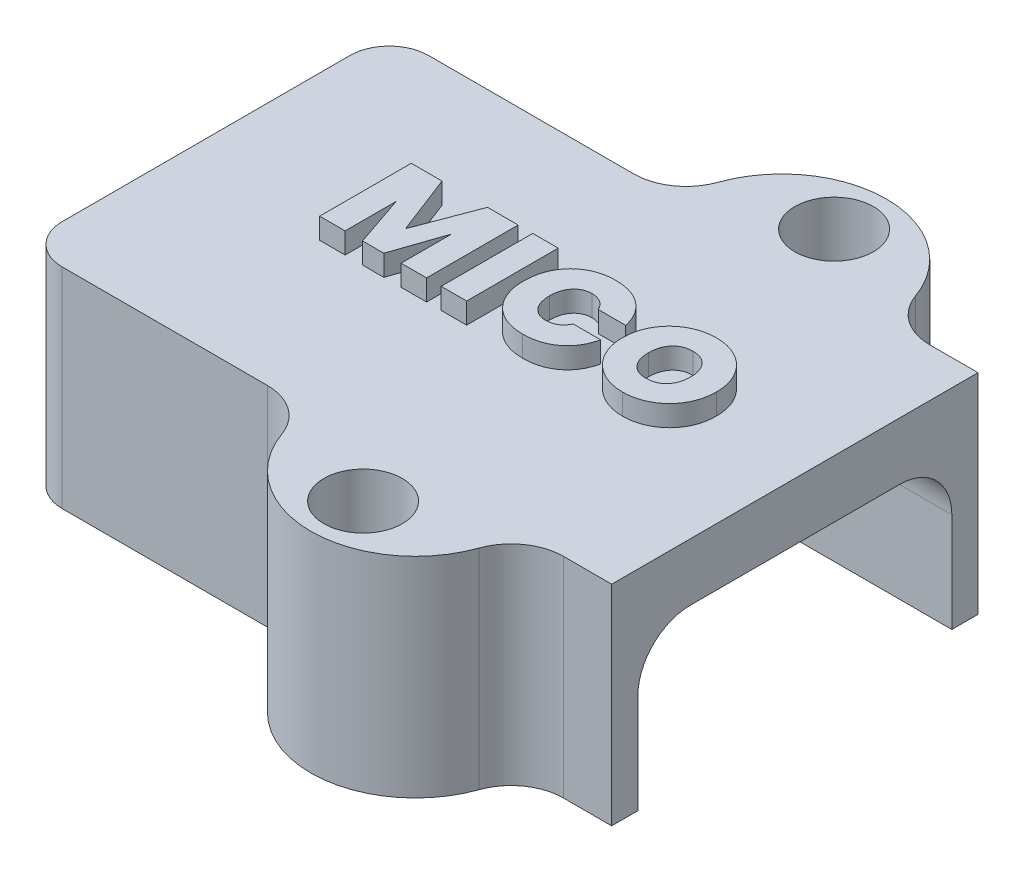
SolidWorks part; units mm, degrees
ref_plane "Front Plane" through (0, 0, 0) normal (0, 0, 1) x (1, 0, 0)
ref_plane "Top Plane" through (0, 0, 0) normal (0, 1, 0) x (1, 0, 0)
ref_plane "Right Plane" through (0, 0, 0) normal (1, 0, 0) x (0, 0, -1)
ref_plane "Plane1" through (0, 19.8512, 0) normal (0, 1, 0) x (1, 0, 0)
sketch "Sketch1" plane through (0, 19.8512, 0) normal (0, 1, 0) x (1, 0, 0)
  line L5 (22.4262, -18.3797) -> (22.4262, -32.3797)
  line L6 (28.4262, -18.3797) -> (20.583, -18.3797) construction
  line L7 (20.583, -32.3797) -> (28.4262, -32.3797) construction
  line L10 (1.4262, -18.3797) -> (9.2693, -18.3797)
  line L11 (22.4262, -18.3797) -> (20.583, -18.3797)
  line L12 (22.4262, -32.3797) -> (20.583, -32.3797)
  line L13 (1.4262, -32.3797) -> (9.2693, -32.3797)
  line L14 (-0.0738, -19.8797) -> (-0.0738, -30.8797)
  circle A15 centre (14.9262, -16.3797) radius 1.5
  circle A16 centre (14.9262, -34.3797) radius 1.5
  arc A17 (18.6974, -17.0464) -> (11.1549, -17.0464) centre (14.9262, -18.3797) ccw
  arc A18 (11.1549, -33.7131) -> (18.6974, -33.7131) centre (14.9262, -32.3797) ccw
  arc A19 (9.2693, -18.3797) -> (11.1549, -17.0464) centre (9.2693, -16.3797) ccw
  arc A20 (20.583, -18.3797) -> (18.6974, -17.0464) centre (20.583, -16.3797) cw
  arc A21 (20.583, -32.3797) -> (18.6974, -33.7131) centre (20.583, -34.3797) ccw
  arc A22 (9.2693, -32.3797) -> (11.1549, -33.7131) centre (9.2693, -34.3797) cw
  arc A23 (1.4262, -18.3797) -> (-0.0738, -19.8797) centre (1.4262, -19.8797) ccw
  arc A24 (1.4262, -32.3797) -> (-0.0738, -30.8797) centre (1.4262, -30.8797) cw
  dimension "D2" = 14
extrude "Boss-Extrude1" add sketch "Sketch1" along normal blind 8
sketch "Sketch3" plane through (0, 27.8512, 0) normal (0, 1, 0) x (1, 0, 0)
  text T0 "MICO" font "Poppins ExtraBold" height 3.5
extrude "Boss-Extrude2" add sketch "Sketch3" along normal blind 0.8
sketch "Sketch4" plane through (-0.0738, 0, 0) normal (-1, 0, 0) x (0, 0, 1)
  line L0 (30.8797, 19.8512) -> (32.3797, 19.8512) construction
  line L1 (19.3797, 25.6512) -> (31.3797, 25.6512)
  line L2 (19.3797, 25.6512) -> (19.3797, 19.8512)
  line L3 (19.3797, 19.8512) -> (31.3797, 19.8512)
  line L4 (31.3797, 25.6512) -> (31.3797, 19.8512)
  line L5 (19.3797, 25.6512) -> (31.3797, 19.8512) construction
  line L6 (19.3797, 19.8512) -> (31.3797, 25.6512) construction
  line L7 (31.3797, 17.3512) -> (31.3797, 19.8512) construction
  point P0 (25.3797, 22.7512)
  dimension "D1" = 12
  dimension "D2" = 5.8
extrude "Cut-Extrude2" cut sketch "Sketch4" against normal through all
fillet "Fillet1" radius 2 2 edges at (11.2191, 25.6512, 19.3797) (11.2191, 25.6512, 31.3797)
